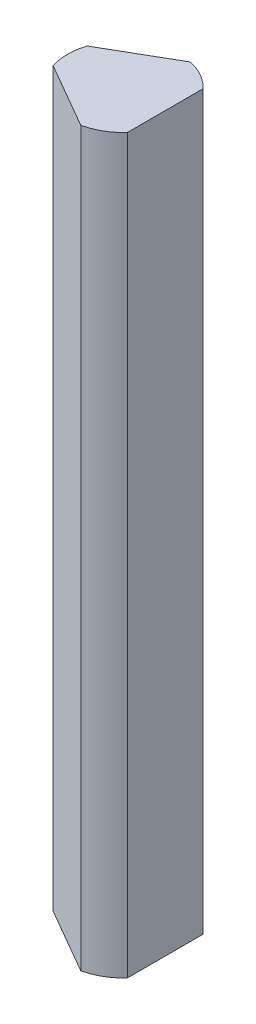
SolidWorks part; units mm, degrees
material "201 Aço inoxidável recozido (SS)"
ref_plane "Plano frontal" through (0, 0, 0) normal (0, 0, 1) x (1, 0, 0)
ref_plane "Plano superior" through (0, 0, 0) normal (0, 1, 0) x (1, 0, 0)
ref_plane "Plano direito" through (0, 0, 0) normal (1, 0, 0) x (0, 0, -1)
sketch "Esboço1" plane through (0, 0, 0) normal (0, 1, 0) x (1, 0, 0)
  line L0 (0.4916, -2.2468) -> (-2.1916, -0.6976)
  line L1 (-2.1916, 0.6976) -> (0.4916, 2.2468)
  line L2 (1.7, -1.5492) -> (1.7, 1.5492)
  line L3 (1.15, -1.9919) -> (-0.85, 1.4722) construction
  line L4 (-2.3, 0) -> (1.7, 0) construction
  arc A0 (0.4916, -2.2468) -> (1.7, -1.5492) centre (0, 0) ccw
  arc A1 (1.7, 1.5492) -> (0.4916, 2.2468) centre (0, 0) ccw
  arc A2 (-2.1916, -0.6976) -> (-2.1916, 0.6976) centre (0, 0) cw
  dimension "D1" = 2.3
  dimension "D2" = 4
extrude "Ressalto-extrusão1" add sketch "Esboço1" along normal blind 30
